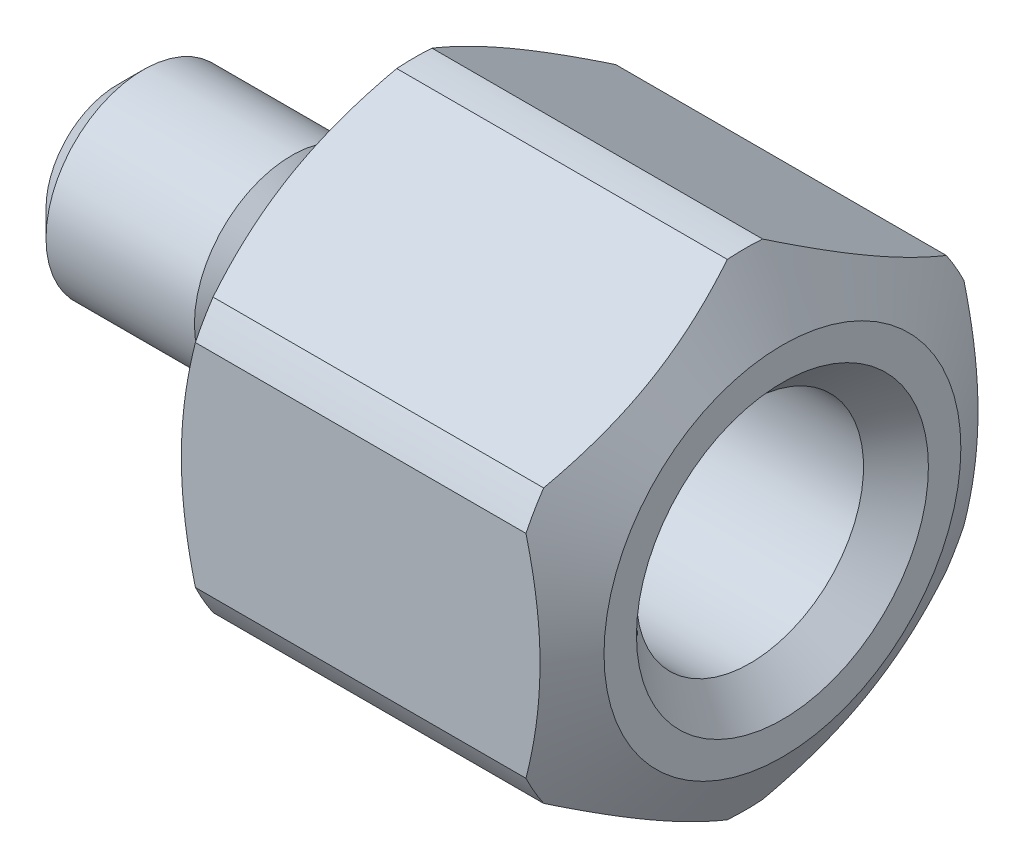
SolidWorks part; units mm, degrees
material "Кованное литое железо"
ref_plane "Спереди" through (0, 0, 0) normal (0, 0, 1) x (1, 0, 0)
ref_plane "Сверху" through (0, 0, 0) normal (0, 1, 0) x (1, 0, 0)
ref_plane "Справа" through (0, 0, 0) normal (1, 0, 0) x (0, 0, -1)
sketch "Эскиз1" plane through (0, 0, 0) normal (0, 0, 1) x (1, 0, 0)
  line L0 (0, 0) -> (39.4386, 0) construction
  line L1 (0, 2) -> (0, 4.4)
  line L2 (1.6, 6) -> (10.75, 6)
  line L3 (10.75, 6) -> (11.8536, 4.8964)
  line L4 (12.2071, 4.75) -> (15, 4.75)
  line L5 (16, 5.75) -> (16, 11)
  line L6 (16, 11) -> (18.3094, 15)
  line L7 (18.3094, 15) -> (38.6906, 15)
  line L8 (38.6906, 15) -> (41, 11)
  line L9 (41, 11) -> (41, 9)
  line L10 (39, 7) -> (26.5, 7)
  line L11 (26.5, 7) -> (25.1464, 8.3536)
  line L12 (24.7929, 8.5) -> (22, 8.5)
  line L13 (21, 7.5) -> (21, 4)
  line L14 (19, 2) -> (0, 2)
  line L15 (0, 4.4) -> (1.6, 6)
  line L16 (21, 4) -> (19, 2)
  line L17 (41, 9) -> (39, 7)
  arc A0 (22, 8.5) -> (21, 7.5) centre (22, 7.5) ccw
  arc A1 (15, 4.75) -> (16, 5.75) centre (15, 5.75) ccw
  arc A2 (25.1464, 8.3536) -> (24.7929, 8.5) centre (24.7929, 8) ccw
  arc A3 (11.8536, 4.8964) -> (12.2071, 4.75) centre (12.2071, 5.25) ccw
  point P4 (0, 6)
  point P13 (41, 7)
  point P17 (21, 2)
  point P26 (21, 8.5)
  point P29 (16, 4.75)
  point P32 (25, 8.5)
  point P35 (12, 4.75)
  dimension "D22" = 1
  dimension "D23" = 0.5
  dimension "D1" = 4
  dimension "D2" = 12
  dimension "D3" = 9.5
  dimension "D4" = 17
  dimension "D5" = 14
  dimension "D6" = 22
  dimension "D7" = 30
  dimension "D8" = 30
  dimension "D9" = 30
  dimension "D10" = 45
  dimension "D11" = 4
  dimension "D12" = 4
  dimension "D13" = 41
  dimension "D14" = 20
  dimension "D15" = 16
  dimension "D16" = 1.6
  dimension "D17" = 45
  dimension "D18" = 2
  dimension "D19" = 45
  dimension "D20" = 2
  dimension "D21" = 45
revolve "Повернуть1" add sketch "Эскиз1" angle 360 about L0
cosmetic thread "Условное изображение резьбы1" parameters "D2"=10.072
cosmetic thread "Условное изображение резьбы2" parameters "D2"=16
sketch "Эскиз2" plane through (41, 0, 0) normal (1, 0, 0) x (0, 0, -1)
  line L1 (0, 15.5885) -> (-13.5, 7.7942)
  line L2 (-13.5, 7.7942) -> (-13.5, -7.7942)
  line L3 (-13.5, -7.7942) -> (0, -15.5885)
  line L4 (0, -15.5885) -> (13.5, -7.7942)
  line L5 (13.5, -7.7942) -> (13.5, 7.7942)
  line L6 (13.5, 7.7942) -> (0, 15.5885)
  circle A0 centre (0, 0) radius 13.5 construction
  dimension "D1" = 27
extrude "Вырез-Вытянуть1" cut sketch "Эскиз2" against normal through all flip side to cut
